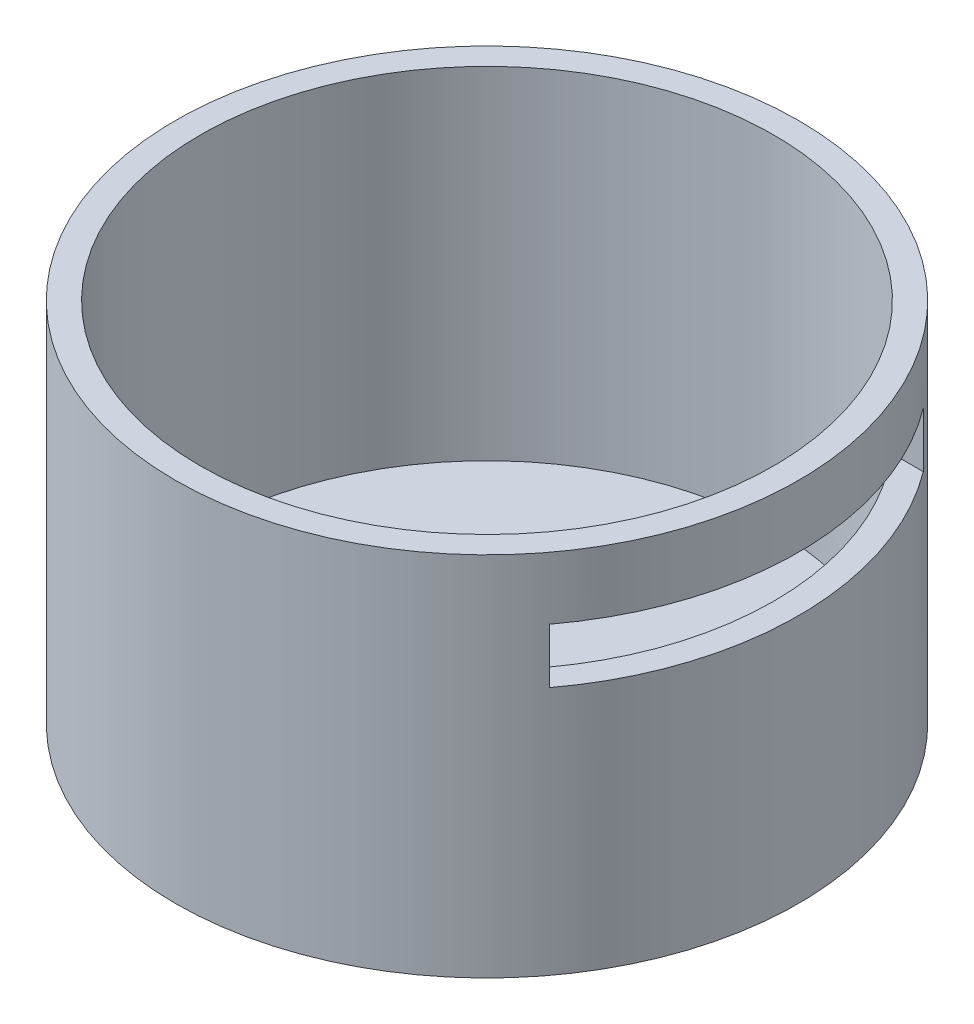
SolidWorks part; units mm, degrees
ref_plane "Front Plane" through (0, 0, 0) normal (0, 0, 1) x (1, 0, 0)
ref_plane "Top Plane" through (0, 0, 0) normal (0, 1, 0) x (1, 0, 0)
ref_plane "Right Plane" through (0, 0, 0) normal (1, 0, 0) x (0, 0, -1)
sketch "Sketch1" plane through (0, 0, 0) normal (0, 1, 0) x (1, 0, 0)
  circle A0 centre (0, 0) radius 12.5
  dimension "D1" = 25
extrude "Boss-Extrude1" add sketch "Sketch1" along normal blind 14.7
shell "Shell1" thickness 1
sketch "Sketch2" plane through (0, 0, 0) normal (1, 0, 0) x (0, 0, -1)
  line L1 (-7.5, 12.2) -> (7.5, 12.2)
  line L2 (-7.5, 12.2) -> (-7.5, 10)
  line L3 (-7.5, 10) -> (7.5, 10)
  line L4 (7.5, 12.2) -> (7.5, 10)
  dimension "D1" = 15
  dimension "D2" = 2.2
  dimension "D3" = 10
  dimension "D4" = 7.5
extrude "Cut-Extrude1" cut sketch "Sketch2" along normal blind 24.7
